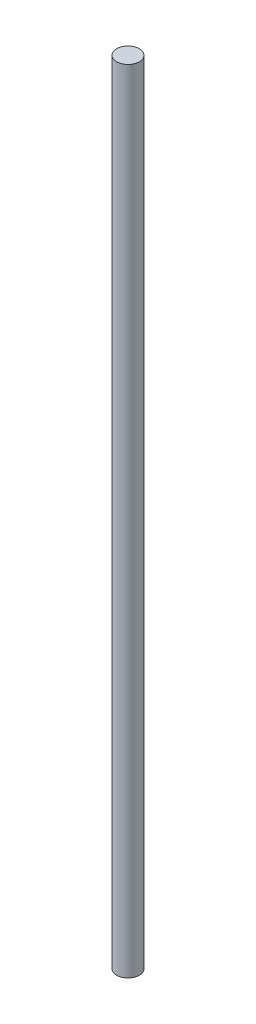
SolidWorks part; units mm, degrees
ref_plane "Front Plane" through (0, 0, 0) normal (0, 0, 1) x (1, 0, 0)
ref_plane "Top Plane" through (0, 0, 0) normal (0, 1, 0) x (1, 0, 0)
ref_plane "Right Plane" through (0, 0, 0) normal (1, 0, 0) x (0, 0, -1)
sketch "Sketch1" plane through (0, 0, 0) normal (0, 1, 0) x (1, 0, 0)
  circle A0 centre (0, 0) radius 4
extrude "Boss-Extrude1" add sketch "Sketch1" along normal blind 280
